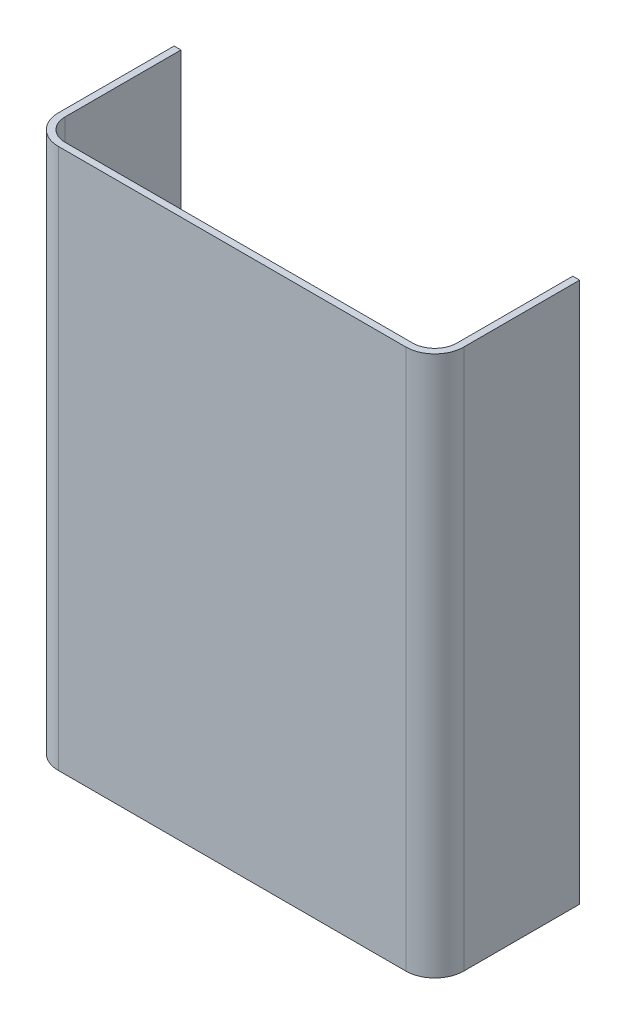
SolidWorks part; units mm, degrees
ref_plane "Front Plane" through (0, 0, 0) normal (0, 0, 1) x (1, 0, 0)
ref_plane "Top Plane" through (0, 0, 0) normal (0, 1, 0) x (1, 0, 0)
ref_plane "Right Plane" through (0, 0, 0) normal (1, 0, 0) x (0, 0, -1)
sketch "Sketch1" plane through (0, 0, 0) normal (0, 1, 0) x (1, 0, 0)
  line L2 (-88.9, 0) -> (-88.9, -50.8)
  line L3 (-76.2, -63.5) -> (76.2, -63.5)
  line L4 (88.9, 0) -> (88.9, -50.8)
  line L7 (85.9, 0) -> (85.9, -50.8)
  line L8 (-76.2, -60.5) -> (76.2, -60.5)
  line L9 (-85.9, 0) -> (-85.9, -50.8)
  line L10 (85.9, 0) -> (88.9, 0)
  line L12 (-88.9, 0) -> (-85.9, 0)
  line L13 (-88.9, 50.8) -> (-88.9, -50.8) construction
  line L14 (-85.9, 50.8) -> (-85.9, -50.8) construction
  line L23 (85.9, 50.8) -> (85.9, -50.8) construction
  line L24 (88.9, 50.8) -> (88.9, -50.8) construction
  line L25 (-76.2, 63.5) -> (76.2, 63.5) construction
  line L26 (-76.2, 60.5) -> (76.2, 60.5) construction
  arc A1 (76.2, -63.5) -> (88.9, -50.8) centre (76.2, -50.8) ccw
  arc A2 (-88.9, -50.8) -> (-76.2, -63.5) centre (-76.2, -50.8) ccw
  arc A5 (76.2, -60.5) -> (85.9, -50.8) centre (76.2, -50.8) ccw
  arc A6 (-85.9, -50.8) -> (-76.2, -60.5) centre (-76.2, -50.8) ccw
  arc A8 (76.2, 63.5) -> (88.9, 50.8) centre (76.2, 50.8) cw construction
  arc A9 (76.2, 60.5) -> (85.9, 50.8) centre (76.2, 50.8) cw construction
  arc A10 (-76.2, 60.5) -> (-85.9, 50.8) centre (-76.2, 50.8) ccw construction
  arc A12 (-76.2, 63.5) -> (-88.9, 50.8) centre (-76.2, 50.8) ccw construction
  point P0 (0, 0)
  dimension "D4" = 3
extrude "Boss-Extrude1" add sketch "Sketch1" along normal blind 237
